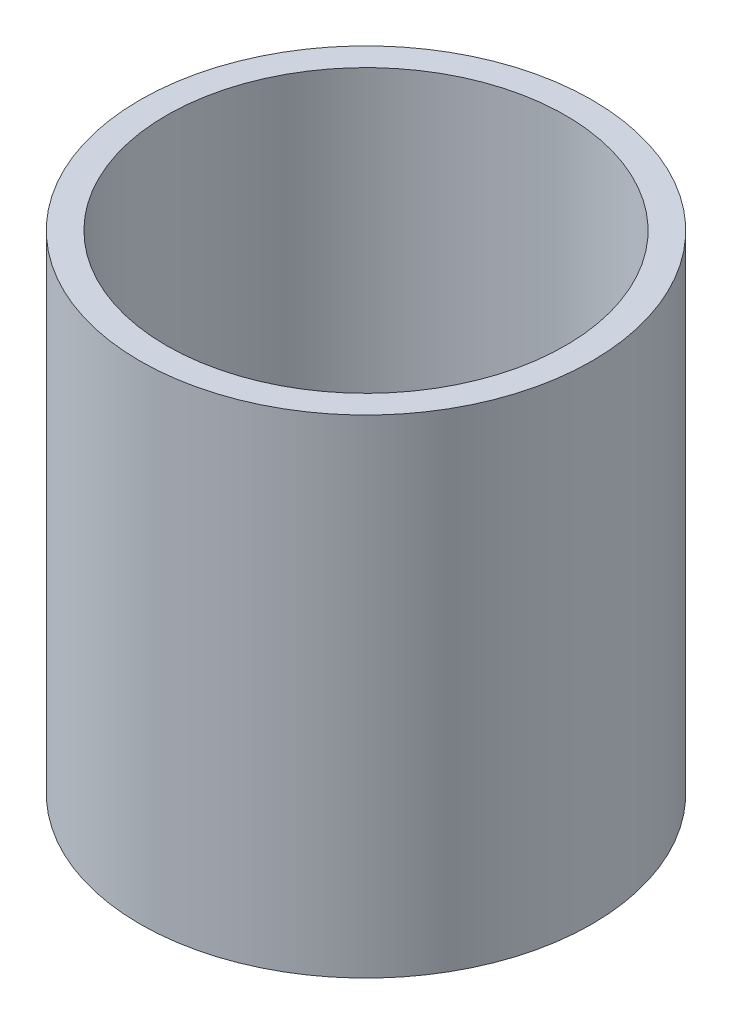
SolidWorks part; units mm, degrees
ref_plane "Front Plane" through (0, 0, 0) normal (0, 0, 1) x (1, 0, 0)
ref_plane "Top Plane" through (0, 0, 0) normal (0, 1, 0) x (1, 0, 0)
ref_plane "Right Plane" through (0, 0, 0) normal (1, 0, 0) x (0, 0, -1)
sketch "Sketch1" plane through (0, 0, 0) normal (0, 1, 0) x (1, 0, 0)
  circle A0 centre (0, 0) radius 22.5
  circle A1 centre (0, 0) radius 25.5
  dimension "D1" = 45
  dimension "D2" = 3
extrude "Boss-Extrude1" add sketch "Sketch1" along normal blind 55
